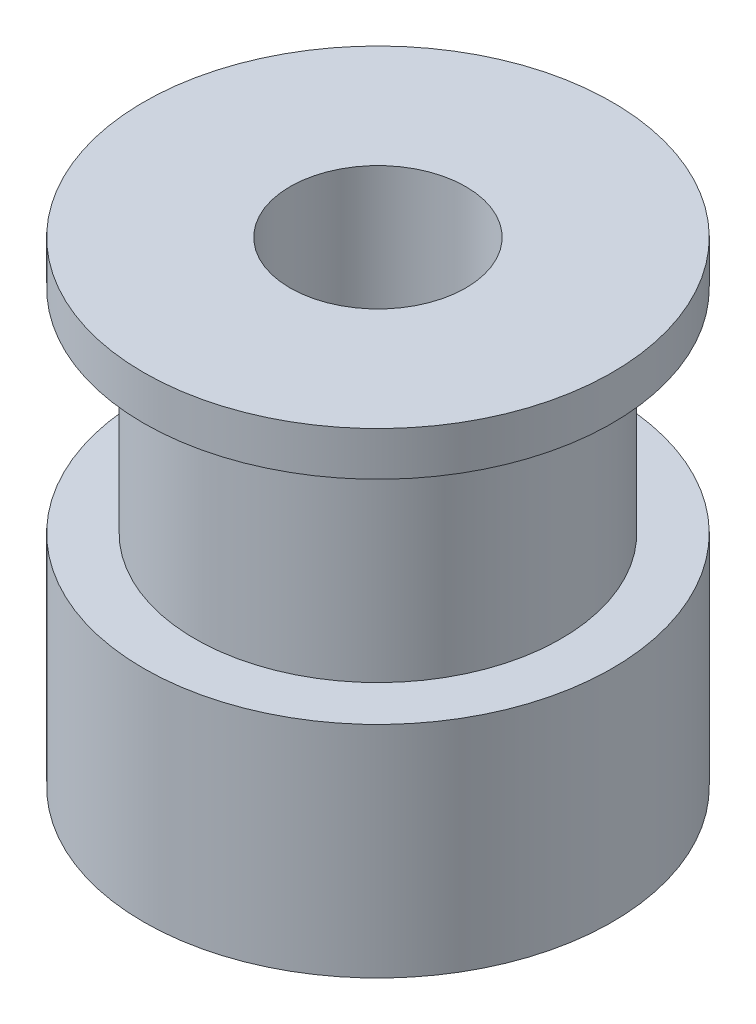
SolidWorks part; units mm, degrees
ref_plane "Front" through (0, 0, 0) normal (0, 0, 1) x (1, 0, 0)
ref_plane "Top" through (0, 0, 0) normal (0, 1, 0) x (1, 0, 0)
ref_plane "Right" through (0, 0, 0) normal (1, 0, 0) x (0, 0, -1)
sketch "Sketch1" plane through (0, 0, 0) normal (0, 1, 0) x (1, 0, 0)
  circle A0 centre (0, 0) radius 8
  circle A1 centre (0, 0) radius 3
  dimension "D1" = 16
  dimension "D2" = 6
extrude "Boss-Extrude1" add sketch "Sketch1" along normal blind 7.5
sketch "Sketch2" plane through (0, 7.5, 0) normal (0, 1, 0) x (1, 0, 0)
  circle A0 centre (0, 0) radius 6.25
  circle A1 centre (0, 0) radius 3 construction
  circle A2 centre (0, 0) radius 3
  dimension "D1" = 12.5
extrude "Boss-Extrude2" add sketch "Sketch2" along normal blind 7.25
sketch "Sketch3" plane through (0, 14.75, 0) normal (0, 1, 0) x (1, 0, 0)
  circle A0 centre (0, 0) radius 3 construction
  circle A1 centre (0, 0) radius 8
  circle A2 centre (0, 0) radius 8
  circle A3 centre (0, 0) radius 3
  dimension "D1" = 0
extrude "Boss-Extrude3" add sketch "Sketch3" along normal blind 1.5
